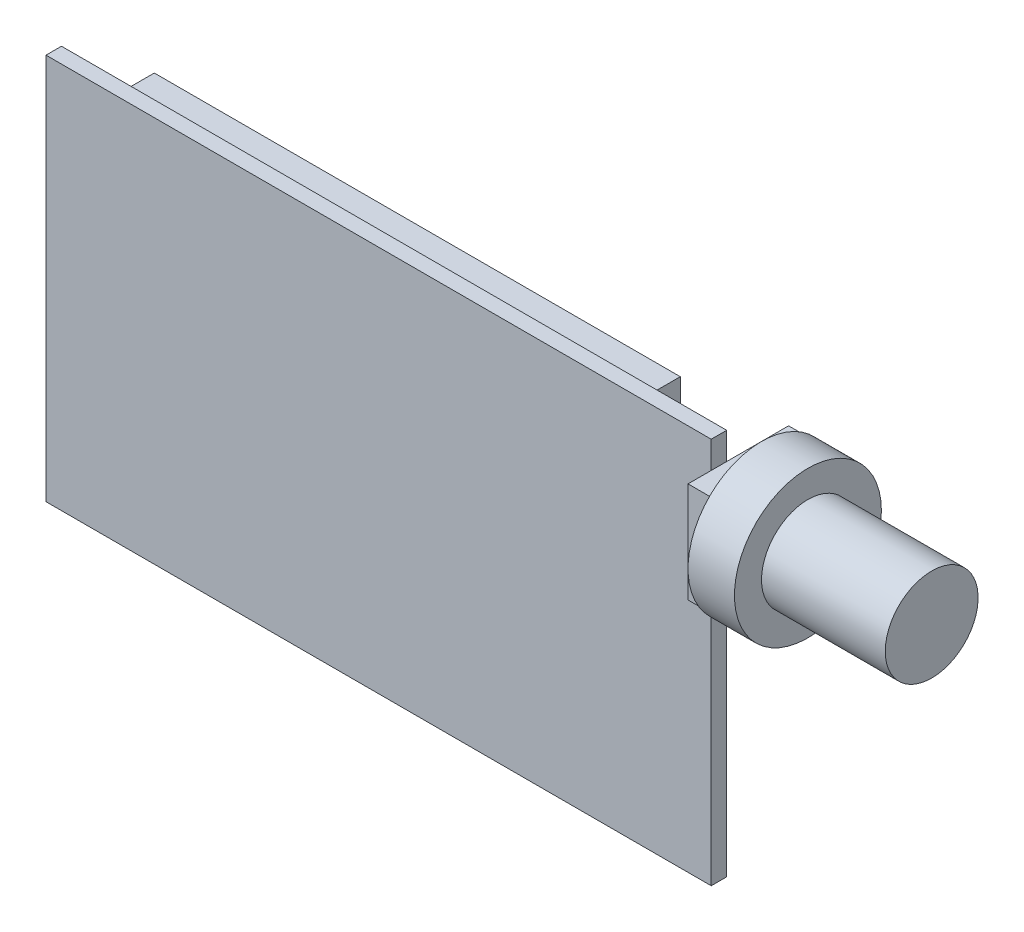
SolidWorks part; units mm, degrees
ref_plane "前视基准面" through (0, 0, 0) normal (0, 0, 1) x (1, 0, 0)
ref_plane "上视基准面" through (0, 0, 0) normal (0, 1, 0) x (1, 0, 0)
ref_plane "右视基准面" through (0, 0, 0) normal (1, 0, 0) x (0, 0, -1)
sketch "草图1" plane through (0, 0, 0) normal (0, 0, 1) x (1, 0, 0)
  line L1 (21.5, -12.5) -> (-21.5, -12.5)
  line L2 (21.5, -12.5) -> (21.5, 12.5)
  line L3 (21.5, 12.5) -> (-21.5, 12.5)
  line L4 (-21.5, -12.5) -> (-21.5, 12.5)
  line L5 (21.5, -12.5) -> (-21.5, 12.5) construction
  line L6 (21.5, 12.5) -> (-21.5, -12.5) construction
  point P0 (0, 0)
  dimension "D1" = 43
  dimension "D2" = 25
extrude "凸台-拉伸1" add sketch "草图1" against normal blind 1
sketch "草图3" plane through (0, 0, 0) normal (0, 0, 1) x (1, 0, 0)
  line L0 (-21.5, 12.5) -> (-21.5, -12.5) construction
  line L1 (-18.5, 11) -> (15.5, 11)
  line L2 (-18.5, 11) -> (-18.5, -11)
  line L3 (-18.5, -11) -> (15.5, -11)
  line L4 (15.5, 11) -> (15.5, -11)
  point P6 (-18.5, 0)
  dimension "D1" = 22
  dimension "D2" = 34
  dimension "D3" = 37
extrude "凸台-拉伸2" add sketch "草图3" against normal blind 4
sketch "草图4" plane through (21.5, 0, 0) normal (1, 0, 0) x (0, 0, -1)
  line L0 (1, 12.5) -> (0, 12.5) construction
  line L1 (-1.5, 4.25) -> (5, 4.25)
  line L2 (-1.5, 4.25) -> (-1.5, 10.75)
  line L3 (-1.5, 10.75) -> (5, 10.75)
  line L4 (5, 4.25) -> (5, 10.75)
  line L5 (-1.5, 4.25) -> (5, 10.75) construction
  line L6 (-1.5, 10.75) -> (5, 4.25) construction
  line L7 (0, -12.5) -> (0, 12.5) construction
  point P0 (1.75, 7.5)
  point P5 (-1.8525, 7.6661)
  dimension "D1" = 6.5
  dimension "D2" = 5
  dimension "D3" = 1.5
extrude "凸台-拉伸3" add sketch "草图4" along normal blind 1.5
sketch "草图5" plane through (21.5, 0, 0) normal (-1, 0, 0) x (0, 0, 1)
  line L0 (-5, 4.25) -> (-5, 10.75) construction
  line L1 (1.5, 4.25) -> (-5, 4.25) construction
  circle A0 centre (-1.75, 7.5) radius 3
  point P4 (0, 0)
  point P5 (-5, 7.5)
  point P8 (-1.75, 4.25)
  dimension "D1" = 6
extrude "凸台-拉伸4" add sketch "草图5" against normal blind 12.5
sketch "草图6" plane through (23, 0, 0) normal (1, 0, 0) x (0, 0, -1)
  circle A0 centre (1.75, 7.5) radius 4.75
  dimension "D1" = 9.5
extrude "凸台-拉伸5" add sketch "草图6" along normal blind 3
